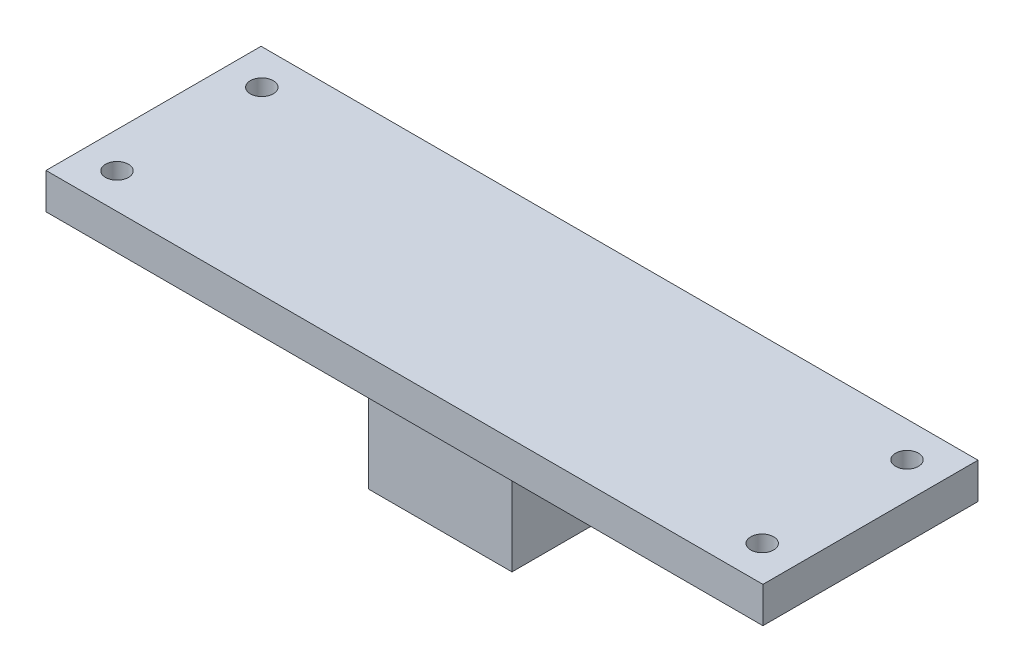
SolidWorks part; units mm, degrees
ref_plane "Спереди" through (0, 0, 0) normal (0, 0, 1) x (1, 0, 0)
ref_plane "Сверху" through (0, 0, 0) normal (0, 1, 0) x (1, 0, 0)
ref_plane "Справа" through (0, 0, 0) normal (1, 0, 0) x (0, 0, -1)
other "Configuration Table"
sketch "Эскиз1" plane through (0, 0, 0) normal (0, 1, 0) x (1, 0, 0)
  line L1 (-39.6717, 20.7934) -> (60.3283, 20.7934)
  line L2 (-39.6717, 20.7934) -> (-39.6717, -9.2066)
  line L3 (-39.6717, -9.2066) -> (60.3283, -9.2066)
  line L4 (60.3283, 20.7934) -> (60.3283, -9.2066)
  dimension "D1" = 100
  dimension "D2" = 30
extrude "Бобышка-Вытянуть1" add sketch "Эскиз1" along normal blind 5
sketch "Эскиз2" plane through (0, 5, 0) normal (0, 1, 0) x (1, 0, 0)
  line L0 (-34.6717, 20.7934) -> (-34.6717, -9.2066)
  line L1 (55.3283, 20.7934) -> (55.3283, -9.2066)
  line L2 (60.3283, 20.7934) -> (-39.6717, 20.7934) construction
  line L3 (-39.6717, -9.2066) -> (60.3283, -9.2066) construction
  line L4 (60.3283, -9.2066) -> (60.3283, 20.7934) construction
  line L5 (-39.6717, 20.7934) -> (-39.6717, -9.2066) construction
  circle A0 centre (-34.6717, 15.8934) radius 1.6
  circle A1 centre (-34.6717, -4.3066) radius 1.6
  circle A2 centre (55.3283, 15.8934) radius 1.6
  circle A3 centre (55.3283, -4.3066) radius 1.6
  dimension "D1" = 3.2
  dimension "D2" = 5
  dimension "D3" = 5
  dimension "D4" = 20.2
  dimension "D5" = 20.2
  dimension "D6" = 4.9
  dimension "D7" = 4.9
  dimension "D8" = 4.9
extrude "Вырез-Вытянуть1" cut sketch "Эскиз2" against normal blind 5 contours A2 | A3 | A1 | A0
sketch "Эскиз3" plane through (0, 0, 0) normal (0, -1, 0) x (1, 0, 0)
  line L0 (60.3283, 9.2066) -> (60.3283, -20.7934) construction
  line L1 (0.3283, 4.2066) -> (20.3283, 4.2066)
  line L2 (0.3283, 4.2066) -> (0.3283, -15.7934)
  line L3 (0.3283, -15.7934) -> (20.3283, -15.7934)
  line L4 (20.3283, 4.2066) -> (20.3283, -15.7934)
  line L5 (-39.6717, -20.7934) -> (-39.6717, 9.2066) construction
  line L6 (-39.6717, 9.2066) -> (60.3283, 9.2066) construction
  line L7 (60.3283, -20.7934) -> (-39.6717, -20.7934) construction
  dimension "D1" = 20
  dimension "D2" = 40
  dimension "D3" = 40
  dimension "D4" = 5
  dimension "D5" = 5
extrude "Бобышка-Вытянуть2" add sketch "Эскиз3" along normal blind 16
sketch "Эскиз4" plane through (0, -16, 0) normal (0, -1, 0) x (1, 0, 0)
  line L0 (20.3283, -15.7934) -> (20.3283, 4.2066) construction
  line L1 (3.8283, 0.7066) -> (16.8283, 0.7066)
  line L2 (3.8283, 0.7066) -> (3.8283, -12.2934)
  line L3 (3.8283, -12.2934) -> (16.8283, -12.2934)
  line L4 (16.8283, 0.7066) -> (16.8283, -12.2934)
  line L5 (0.3283, 4.2066) -> (0.3283, -15.7934) construction
  line L6 (0.3283, -15.7934) -> (20.3283, -15.7934) construction
  dimension "D1" = 13
  dimension "D2" = 3.5
  dimension "D3" = 3.5
  dimension "D4" = 3.5
extrude "Вырез-Вытянуть2" cut sketch "Эскиз4" against normal blind 16
sketch "Эскиз5" plane through (20.3283, 0, 0) normal (1, 0, 0) x (0, 0, -1)
  line L0 (-4.2066, -7) -> (15.7934, -7)
  line L1 (15.7934, -16) -> (15.7934, 0) construction
  line L2 (-4.2066, -16) -> (-4.2066, 0) construction
  line L3 (15.7934, 0) -> (-4.2066, 0) construction
  circle A0 centre (5.7934, -7) radius 2.5
  point P6 (0, 0)
  point P9 (0, 0)
  dimension "D1" = 5
  dimension "D2" = 7
extrude "Вырез-Вытянуть3" cut sketch "Эскиз5" against normal blind 10 contours A0
